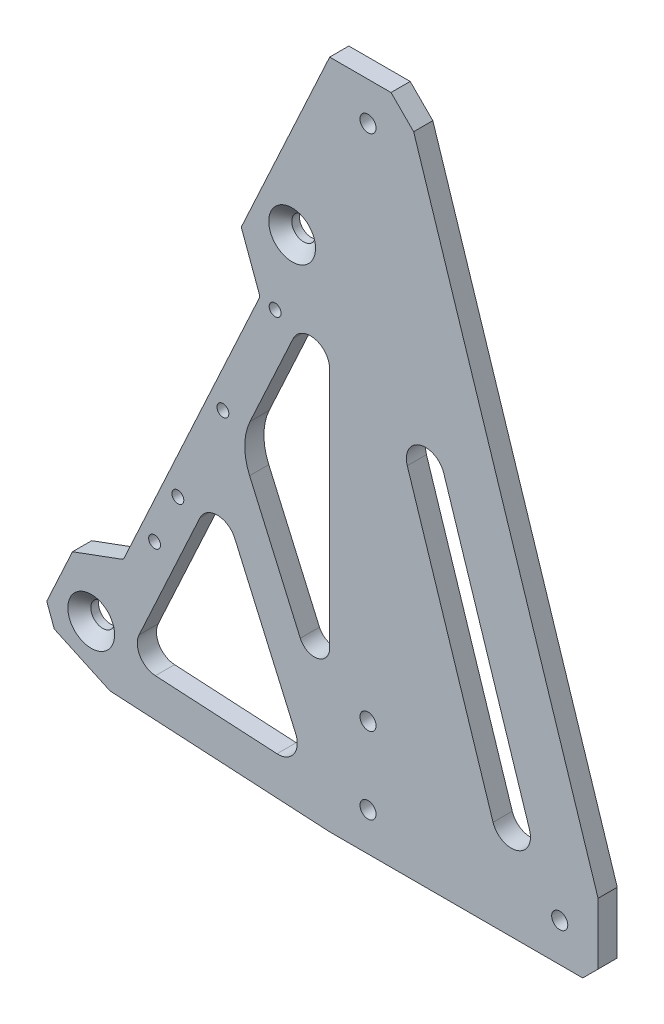
SolidWorks part; units mm, degrees
ref_plane "前视基准面" through (0, 0, 0) normal (0, 0, 1) x (1, 0, 0)
ref_plane "上视基准面" through (0, 0, 0) normal (0, 1, 0) x (1, 0, 0)
ref_plane "右视基准面" through (0, 0, 0) normal (1, 0, 0) x (0, 0, -1)
sketch "草图1" plane through (0, 0, 0) normal (0, 0, 1) x (1, 0, 0)
  line L0 (-35, 87.5) -> (-35, -87.5)
  line L1 (-35, -87.5) -> (35, -87.5)
  line L2 (35, -87.5) -> (35, -67.5)
  line L3 (35, -67.5) -> (-15, 87.5)
  line L4 (-15, 87.5) -> (-35, 87.5)
  line L5 (25, -77.5) -> (-25, -77.5) construction
  line L6 (-25, -77.5) -> (-25, -57.5) construction
  line L7 (-25, -57.5) -> (-25, 77.5) construction
  circle A0 centre (-25, -77.5) radius 2.1
  circle A1 centre (25, -77.5) radius 2.1
  circle A2 centre (-25, 77.5) radius 2.1
  circle A3 centre (-25, -57.5) radius 2.1
  point P0 (-35, 0)
  point P7 (0, -87.5)
  dimension "D3" = 10
  dimension "D6" = 10
  dimension "D7" = 4.2
  dimension "D1" = 20
  dimension "D2" = 20
  dimension "D4" = 10
  dimension "D5" = 10
  dimension "D8" = 175
  dimension "D9" = 70
  dimension "D10" = 20
extrude "凸台-拉伸1" add sketch "草图1" along normal mid plane 5
sketch "草图2" plane through (0, 0, -2.5) normal (0, 0, -1) x (-1, 0, 0)
  line L0 (-12.3723, -62.5) -> (10, 6.854) construction
  line L1 (-17.1308, -60.965) -> (5.2415, 8.389)
  line L2 (-7.6137, -64.035) -> (14.7585, 5.319)
  line L3 (-35, -67.5) -> (15, 87.5) construction
  line L5 (35, 87.5) -> (35, -87.5) construction
  arc A0 (-17.1308, -60.965) -> (-7.6137, -64.035) centre (-12.3723, -62.5) ccw
  arc A1 (14.7585, 5.319) -> (5.2415, 8.389) centre (10, 6.854) ccw
  circle A3 centre (-25, -77.5) radius 2.1 construction
  point P2 (-1.1861, -27.823)
  dimension "D2" = 5
  dimension "D3" = 25
  dimension "D4" = 15
  dimension "D1" = 15
extrude "切除-拉伸1" cut sketch "草图2" against normal through all
sketch "草图3" plane through (0, 0, -2.5) normal (0, 0, -1) x (-1, 0, 0)
  line L0 (35, -87.5) -> (92.3029, -84.3033)
  line L1 (92.3029, -84.3033) -> (110.4606, -75.9188)
  line L2 (110.4606, -75.9188) -> (35, 87.5)
  line L3 (110.4606, -75.9188) -> (115, -73.8227) construction
  line L6 (115, -73.8227) -> (39.5394, 89.5961) construction
  line L7 (39.5394, 89.5961) -> (35, 87.5) construction
  line L8 (35, 87.5) -> (35, -87.5) construction
  line L9 (15, 87.5) -> (35, 87.5) construction
  line L10 (35, 87.5) -> (35, -87.5)
  dimension "D1" = 5
  dimension "D2" = 80
  dimension "D3" = 180
  dimension "D4" = 20
extrude "凸台-拉伸2" add sketch "草图3" against normal blind 5
sketch "草图5" plane through (0, 0, -2.5) normal (0, 0, -1) x (-1, 0, 0)
  line L0 (35, 39.793) -> (58.5981, -11.3116)
  line L1 (87.7943, -74.5393) -> (40.598, -77.1722)
  line L2 (35, -65.049) -> (35, 39.793)
  line L3 (35, -87.5) -> (92.3029, -84.3033) construction
  line L4 (110.4606, -75.9188) -> (35, 87.5) construction
  line L5 (35, -77.4845) -> (61.3971, -17.3731) construction
  line L6 (40.598, -77.1722) -> (64.1961, -23.4347)
  line L7 (35, -65.049) -> (58.5981, -11.3116)
  line L8 (30.422, -75.4741) -> (56.8191, -15.3628) construction
  line L9 (39.578, -79.4948) -> (65.9752, -19.3835) construction
  line L10 (64.1961, -23.4347) -> (87.7943, -74.5393)
  circle A0 centre (25, -57.5) radius 2.1 construction
  dimension "D1" = 20
  dimension "D2" = 10
  dimension "D3" = 10
  dimension "D4" = 5
  dimension "D5" = 5
extrude "切除-拉伸2" cut sketch "草图5" against normal through all
fillet "圆角1" radius 5 4 edges at (-87.7943, -74.5393, 0) (-64.1961, -23.4347, 0) (-40.598, -77.1722, 0) (-35, 39.793, 0)
fillet "圆角2" radius 4 1 edges at (-35, -65.049, 0)
fillet "圆角3" radius 15 1 edges at (-58.5981, -11.3116, 0)
chamfer "倒角1" distance 4 angle 45 3 edges at (35, -87.5, 0) (-110.4606, -75.9188, 0) (-15, 87.5, 0)
chamfer "倒角2" distance 2 angle 45 4 edges at (27.1, -77.5, -2.5) (-22.9, -77.5, -2.5) (-22.9, -57.5, -2.5) (-22.9, 77.5, -2.5)
sketch "草图6" plane through (0, 0, -2.5) normal (0, 0, -1) x (-1, 0, 0)
  line L0 (44.7863, 42.453) -> (97.1895, -71.0322) construction
  line L2 (108.7837, -72.2873) -> (35, 87.5) construction
  line L3 (92.3029, -84.3033) -> (106.8291, -77.5957) construction
  line L4 (44.5394, 19.1343) -> (35, 39.793) construction
  line L5 (35, 17.0381) -> (35, 39.793) construction
  line L6 (55.7658, -5.1779) -> (44.5394, 19.1343) construction
  line L7 (35, 39.793) -> (53.1576, 48.1775) construction
  circle A0 centre (97.1895, -71.0322) radius 3.1
  circle A2 centre (44.7863, 42.453) radius 3.1
  dimension "D1" = 10
  dimension "D2" = 10
  dimension "D4" = 6.2
  dimension "D3" = 125
extrude "切除-拉伸3" cut sketch "草图6" against normal through all
sketch "草图7" plane through (0, 0, 2.5) normal (0, 0, 1) x (1, 0, 0)
  line L0 (-58.0574, 37.5665) -> (-53.1708, 24.2954)
  line L1 (-108.7837, -72.2873) -> (-35, 87.5) construction
  line L2 (-53.1708, 24.2954) -> (-88.805, -52.8746)
  line L3 (-88.805, -52.8746) -> (-102.0761, -57.7611)
  line L4 (-102.0761, -57.7611) -> (-58.0574, 37.5665)
  line L6 (-55.7658, -5.1779) -> (-44.5394, 19.1343) construction
  line L7 (-102.0761, -57.7611) -> (-83.9184, -66.1457) construction
  line L8 (-84.7104, -67.8606) -> (-68.8501, -33.5133) construction
  line L9 (-58.0574, 37.5665) -> (-39.8998, 29.182) construction
  circle A4 centre (-44.7863, 42.453) radius 3.1 construction
  circle A5 centre (-97.1895, -71.0322) radius 3.1 construction
  dimension "D2" = 10
  dimension "D3" = 10
  dimension "D1" = 10
extrude "切除-拉伸4" cut sketch "草图7" against normal through all
sketch "草图8" plane through (0, 0, 2.5) normal (0, 0, 1) x (1, 0, 0)
  line L0 (-80.6668, -44.7917) -> (-74.588, -31.6275) construction
  line L1 (-74.588, -31.6275) -> (-62.8497, -6.2068) construction
  line L2 (-62.8497, -6.2068) -> (-49.2249, 23.2994) construction
  line L3 (-88.805, -52.8746) -> (-53.1708, 24.2954) construction
  line L4 (-70.9879, -14.2896) -> (-67.3564, -15.9665) construction
  circle A0 centre (-49.2249, 23.2994) radius 1.55
  circle A1 centre (-62.8497, -6.2068) radius 1.55
  circle A2 centre (-74.588, -31.6275) radius 1.55
  circle A3 centre (-80.6668, -44.7917) radius 1.55
  dimension "D2" = 3.1
  dimension "D1" = 4
  dimension "D3" = 10.75
  dimension "D4" = 28
  dimension "D5" = 14.5
  dimension "D6" = 32.5
extrude "切除-拉伸5" cut sketch "草图8" against normal through all
fillet "圆角4" radius 1 2 edges at (-88.805, -52.8746, 0) (-53.1708, 24.2954, 0)
chamfer "倒角3" distance 3 angle 45 2 edges at (-100.2895, -71.0322, 2.5) (-47.8863, 42.453, 2.5)
